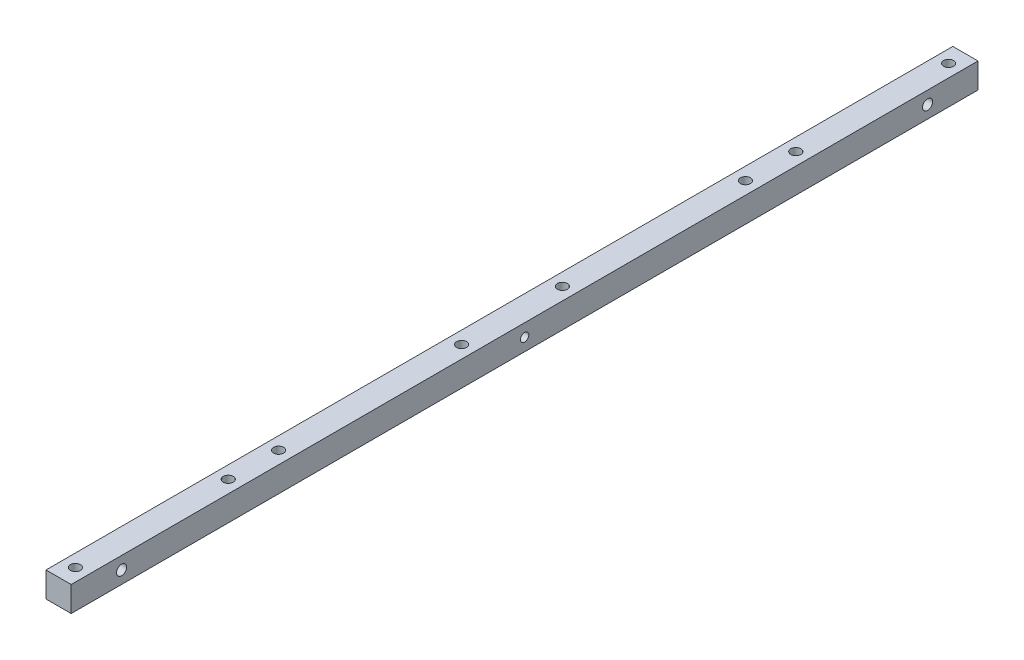
SolidWorks part; units mm, degrees
material "3.3535 (EN-AW 5754)"
ref_plane "Plan de face" through (0, 0, 0) normal (0, 0, 1) x (1, 0, 0)
ref_plane "Plan de dessus" through (0, 0, 0) normal (0, 1, 0) x (1, 0, 0)
ref_plane "Plan de droite" through (0, 0, 0) normal (1, 0, 0) x (0, 0, -1)
sketch "Esquisse1" plane through (0, 0, 0) normal (0, 0, 1) x (1, 0, 0)
  line L1 (-3.75, -3.75) -> (3.75, -3.75)
  line L2 (-3.75, -3.75) -> (-3.75, 3.75)
  line L3 (-3.75, 3.75) -> (3.75, 3.75)
  line L4 (3.75, -3.75) -> (3.75, 3.75)
  line L5 (-3.75, -3.75) -> (3.75, 3.75) construction
  line L6 (-3.75, 3.75) -> (3.75, -3.75) construction
  point P0 (0, 0)
  dimension "D1" = 7.5
  dimension "D2" = 7.5
extrude "Boss.-Extru.1" add sketch "Esquisse1" along normal mid plane 270
sketch "Esquisse2" plane through (3.75, 0, 0) normal (1, 0, 0) x (0, 0, -1)
  line L0 (0, 4.125) -> (0, -4.125) construction
  circle A0 centre (-120, 0) radius 1.5
  circle A1 centre (120, 0) radius 1.5
  circle A2 centre (0, 0) radius 1.25
  dimension "D1" = 240
  dimension "D2" = 3
  dimension "D3" = 2.5
extrude "Enlèv. mat.-Extru.1" cut sketch "Esquisse2" against normal through all
sketch "Esquisse3" plane through (0, 3.75, 0) normal (0, 1, 0) x (1, 0, 0)
  line L0 (0, -69.5) -> (0, -84.5) construction
  line L1 (-4.125, 0) -> (4.125, 0) construction
  circle A0 centre (0, -69.5) radius 1.5
  circle A1 centre (0, -84.5) radius 1.5
  circle A2 centre (0, 84.5) radius 1.5
  circle A3 centre (0, 69.5) radius 1.5
  circle A4 centre (0, -130) radius 1.5
  circle A5 centre (0, 130) radius 1.5
  circle A6 centre (0, -15) radius 1.5
  circle A7 centre (0, 15) radius 1.5
  point P11 (0, -77)
  dimension "D1" = 15
  dimension "D2" = 3
  dimension "D4" = 260
  dimension "D5" = 30
  dimension "D3" = 77
extrude "Enlèv. mat.-Extru.2" cut sketch "Esquisse3" against normal through all
